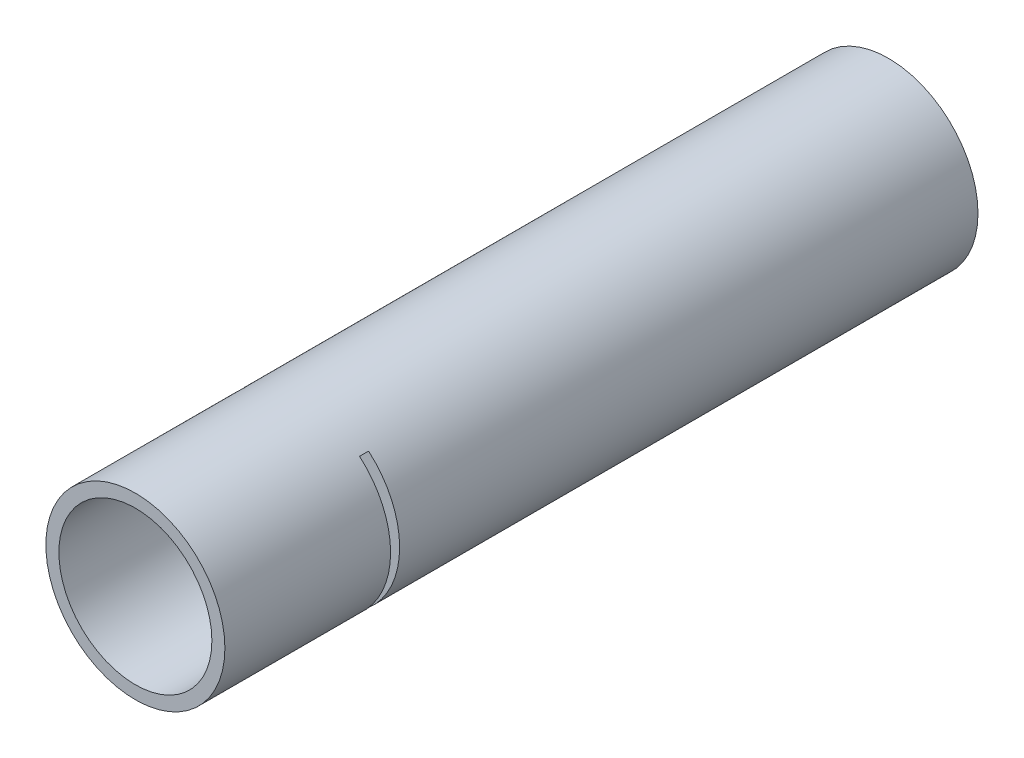
SolidWorks part; units mm, degrees
ref_plane "Alzado" through (0, 0, 0) normal (0, 0, 1) x (1, 0, 0)
ref_plane "Planta" through (0, 0, 0) normal (0, 1, 0) x (1, 0, 0)
ref_plane "Vista lateral" through (0, 0, 0) normal (1, 0, 0) x (0, 0, -1)
sketch "Croquis1" plane through (0, 0, 0) normal (0, 0, 1) x (1, 0, 0)
  circle A0 centre (0, 0) radius 25.4
  circle A1 centre (0, 0) radius 29.72
  dimension "D1" = 59.44
  dimension "D2" = 50.8
extrude "Saliente-Extruir1" add sketch "Croquis1" along normal blind 250
sketch "Croquis2" plane through (0, 0, 0) normal (1, 0, 0) x (0, 0, -1)
  line L1 (-195, -22.5) -> (-192, -22.5)
  line L2 (-195, -22.5) -> (-195, 22.5)
  line L3 (-195, 22.5) -> (-192, 22.5)
  line L4 (-192, -22.5) -> (-192, 22.5)
  line L5 (-195, -22.5) -> (-192, 22.5) construction
  line L6 (-195, 22.5) -> (-192, -22.5) construction
  line L7 (-250, 29.72) -> (-250, -29.72) construction
  point P0 (-193.5, 0)
  point P5 (0, 0)
  dimension "D1" = 45
  dimension "D2" = 3
  dimension "D3" = 55
extrude "Cortar-Extruir1" cut sketch "Croquis2" against normal through all both and the other way through all
